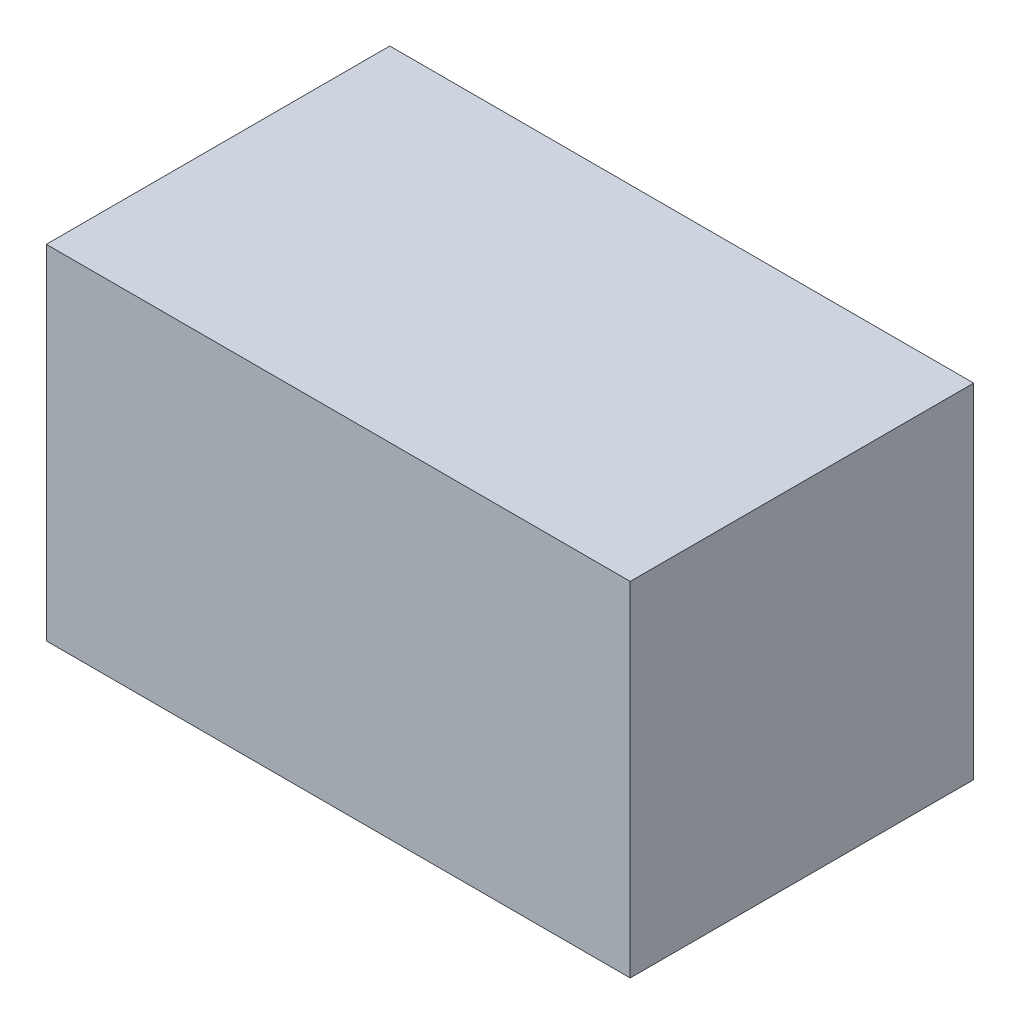
SolidWorks part; units mm, degrees
ref_plane "Front Plane" through (0, 0, 0) normal (0, 0, 1) x (1, 0, 0)
ref_plane "Top Plane" through (0, 0, 0) normal (0, 1, 0) x (1, 0, 0)
ref_plane "Right Plane" through (0, 0, 0) normal (1, 0, 0) x (0, 0, -1)
sketch "Sketch1" plane through (0, 0, 0) normal (0, 1, 0) x (1, 0, 0)
  line L1 (0, 0) -> (17, 0)
  line L2 (0, 0) -> (0, 10)
  line L3 (0, 10) -> (17, 10)
  line L4 (17, 0) -> (17, 10)
  dimension "D1" = 17
  dimension "D2" = 10
extrude "Boss-Extrude1" add sketch "Sketch1" along normal blind 10
